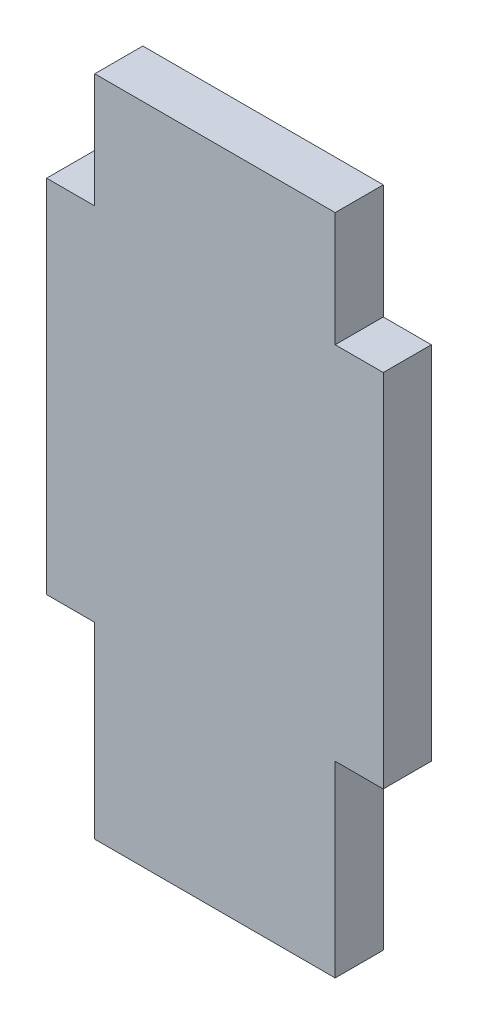
SolidWorks part; units mm, degrees
ref_plane "Front Plane" through (0, 0, 0) normal (0, 0, 1) x (1, 0, 0)
ref_plane "Top Plane" through (0, 0, 0) normal (0, 1, 0) x (1, 0, 0)
ref_plane "Right Plane" through (0, 0, 0) normal (1, 0, 0) x (0, 0, -1)
sketch "Sketch1" plane through (0, 0, 0) normal (0, 0, 1) x (1, 0, 0)
  line L0 (48.6472, 141.0452) -> (43.5672, 141.0452)
  line L1 (18.1672, 146.0233) -> (18.1672, 153.1353)
  line L2 (48.6472, 141.0452) -> (48.6472, 102.9452)
  line L3 (18.1672, 153.1353) -> (43.5672, 153.1353)
  line L4 (48.6472, 102.9452) -> (43.5672, 102.9452)
  line L5 (43.5672, 102.9452) -> (43.5672, 95.3054)
  line L7 (18.1672, 95.3054) -> (18.1672, 102.9452)
  line L8 (18.1672, 102.9452) -> (13.0872, 102.9452)
  line L9 (13.0872, 102.9452) -> (13.0872, 141.0452)
  line L10 (13.0872, 141.0452) -> (18.1672, 141.0452)
  line L11 (18.1672, 141.0452) -> (18.1672, 146.0233)
  line L13 (43.5672, 146.0233) -> (43.5672, 141.0452)
  line L14 (43.5672, 153.1353) -> (43.5672, 146.0233)
  line L15 (18.1672, 95.3054) -> (18.1672, 83.1134)
  line L16 (18.1672, 83.1134) -> (43.5672, 83.1134)
  line L17 (43.5672, 83.1134) -> (43.5672, 95.3054)
  dimension "D1" = 7.112
  dimension "D2" = 12.192
extrude "Boss-Extrude1" add sketch "Sketch1" along normal blind 5.08 contours L9 L10 L11 L1 L3 L14 L13 L0 L2 L4 L5 L17 L16 L15 L7 L8
